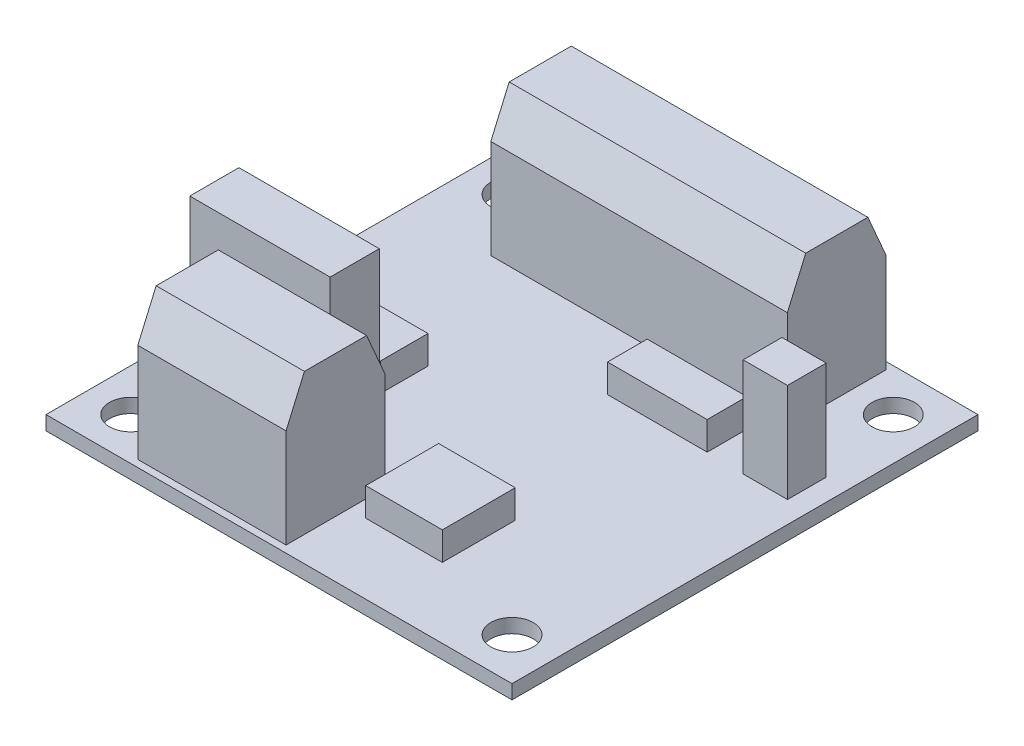
SolidWorks part; units mm, degrees
ref_plane "Front Plane" through (0, 0, 0) normal (0, 0, 1) x (1, 0, 0)
ref_plane "Top Plane" through (0, 0, 0) normal (0, 1, 0) x (1, 0, 0)
ref_plane "Right Plane" through (0, 0, 0) normal (1, 0, 0) x (0, 0, -1)
sketch "Sketch1" plane through (0, 0, 0) normal (0, 1, 0) x (1, 0, 0)
  line L0 (0, 10.3298) -> (0, 0) construction
  line L1 (-16.5, -16.5) -> (16.5, -16.5)
  line L2 (-16.5, -16.5) -> (-16.5, 16.5)
  line L3 (-16.5, 16.5) -> (16.5, 16.5)
  line L4 (16.5, -16.5) -> (16.5, 16.5)
  line L5 (-16.5, -16.5) -> (16.5, 16.5) construction
  line L6 (-16.5, 16.5) -> (16.5, -16.5) construction
  line L7 (0, 0) -> (-11.1618, 0) construction
  circle A0 centre (-13.5, 13.5) radius 1.5
  circle A1 centre (-13.5, -13.5) radius 1.5
  circle A2 centre (13.5, -13.5) radius 1.5
  circle A3 centre (13.5, 13.5) radius 1.5
  point P0 (0, 0)
  dimension "D3" = 3
  dimension "D1" = 33
  dimension "D2" = 33
  dimension "D4" = 3
  dimension "D5" = 3
extrude "Boss-Extrude1" add sketch "Sketch1" along normal mid plane 1
sketch "Sketch2" plane through (0, 0.5, 0) normal (0, 1, 0) x (1, 0, 0)
  line L0 (16.5, 16.5) -> (-16.5, 16.5) construction
  line L1 (-10.5, 16) -> (10.5, 16)
  line L2 (-10.5, 16) -> (-10.5, 9)
  line L3 (-10.5, 9) -> (10.5, 9)
  line L4 (10.5, 16) -> (10.5, 9)
  line L5 (16.5, -16.5) -> (16.5, 16.5) construction
  line L7 (-33.314, 0) -> (0, 0) construction
  line L9 (-10.5, -9) -> (0, -9)
  line L10 (-10.5, -16) -> (-10.5, -9)
  line L11 (-10.5, -16) -> (0, -16)
  line L12 (0, -9) -> (0, -16)
  line L13 (-14.812, -4.5249) -> (-4.873, -4.5249)
  line L14 (-14.812, -4.5249) -> (-14.812, -8.0061)
  line L15 (-14.812, -8.0061) -> (-4.873, -8.0061)
  line L16 (-4.873, -4.5249) -> (-4.873, -8.0061)
  dimension "D1" = 0.5
  dimension "D4" = 6
extrude "Boss-Extrude2" add sketch "Sketch2" along normal blind 10
sketch "Sketch3" plane through (0, 0.5, 0) normal (0, 1, 0) x (1, 0, 0)
  line L1 (1.1763, -6.3719) -> (6.6006, -6.3719)
  line L2 (1.1763, -6.3719) -> (1.1763, -11.5347)
  line L3 (1.1763, -11.5347) -> (6.6006, -11.5347)
  line L4 (6.6006, -6.3719) -> (6.6006, -11.5347)
  line L5 (2.1566, 7.4175) -> (9.2147, 7.4175)
  line L6 (2.1566, 7.4175) -> (2.1566, 4.6073)
  line L7 (2.1566, 4.6073) -> (9.2147, 4.6073)
  line L8 (9.2147, 7.4175) -> (9.2147, 4.6073)
  line L9 (-9.7375, 0) -> (-5.9471, 0)
  line L10 (-9.7375, 0) -> (-9.7375, -3.3656)
  line L11 (-9.7375, -3.3656) -> (-5.9471, -3.3656)
  line L12 (-5.9471, 0) -> (-5.9471, -3.3656)
extrude "Boss-Extrude3" add sketch "Sketch3" along normal blind 2
sketch "Sketch4" plane through (0, 0.5, 0) normal (0, 1, 0) x (1, 0, 0)
  line L1 (11.8288, 7.2868) -> (14.9657, 7.2868)
  line L2 (11.8288, 7.2868) -> (11.8288, 4.542)
  line L3 (11.8288, 4.542) -> (14.9657, 4.542)
  line L4 (14.9657, 7.2868) -> (14.9657, 4.542)
extrude "Boss-Extrude4" add sketch "Sketch4" along normal blind 7
sketch "Sketch5" plane through (10.5, 0, 0) normal (1, 0, 0) x (0, 0, -1)
  line L0 (12.5, 10.5) -> (12.5, 14.018) construction
  line L1 (9, 10.5) -> (16, 10.5) construction
  line L2 (10.3, 10.5) -> (9, 10.5)
  line L3 (9, 10.5) -> (9, 7.5)
  line L4 (9, 10.5) -> (9, 0.5) construction
  line L5 (9, 7.5) -> (10.3, 10.5)
  line L6 (16, 7.5) -> (14.7, 10.5)
  line L7 (16, 10.5) -> (16, 7.5)
  line L8 (14.7, 10.5) -> (16, 10.5)
  line L9 (0, 17.2589) -> (0, 0) construction
  line L10 (10.3, 10.5) -> (9, 10.5)
  line L11 (9, 10.5) -> (9, 7.5)
  line L12 (9, 7.5) -> (10.3, 10.5)
  line L13 (16, 7.5) -> (14.7, 10.5)
  line L14 (16, 10.5) -> (16, 7.5)
  line L15 (14.7, 10.5) -> (16, 10.5)
  line L16 (-12.5, 10.5) -> (-12.5, 14.018) construction
  line L17 (-14.7, 10.5) -> (-16, 10.5)
  line L18 (-16, 10.5) -> (-16, 7.5)
  line L19 (-16, 7.5) -> (-14.7, 10.5)
  line L20 (-9, 7.5) -> (-10.3, 10.5)
  line L21 (-9, 10.5) -> (-9, 7.5)
  line L22 (-10.3, 10.5) -> (-9, 10.5)
  line L23 (-14.7, 10.5) -> (-16, 10.5)
  line L24 (-16, 10.5) -> (-16, 7.5)
  line L25 (-16, 7.5) -> (-14.7, 10.5)
  line L26 (-9, 7.5) -> (-10.3, 10.5)
  line L27 (-9, 10.5) -> (-9, 7.5)
  line L28 (-10.3, 10.5) -> (-9, 10.5)
  line M6 (16, 0.5) -> (16, 10.5)
  line M7 (16, 10.5) -> (9, 10.5)
  line M8 (9, 10.5) -> (9, 0.5)
  dimension "D1" = 1.3
  dimension "D2" = 3
extrude "Cut-Extrude1" cut sketch "Sketch5" against normal blind 24 contours L18 L19 L17 | L22 L20 L21 | L5 M8 M7 | L6 M6 M7
